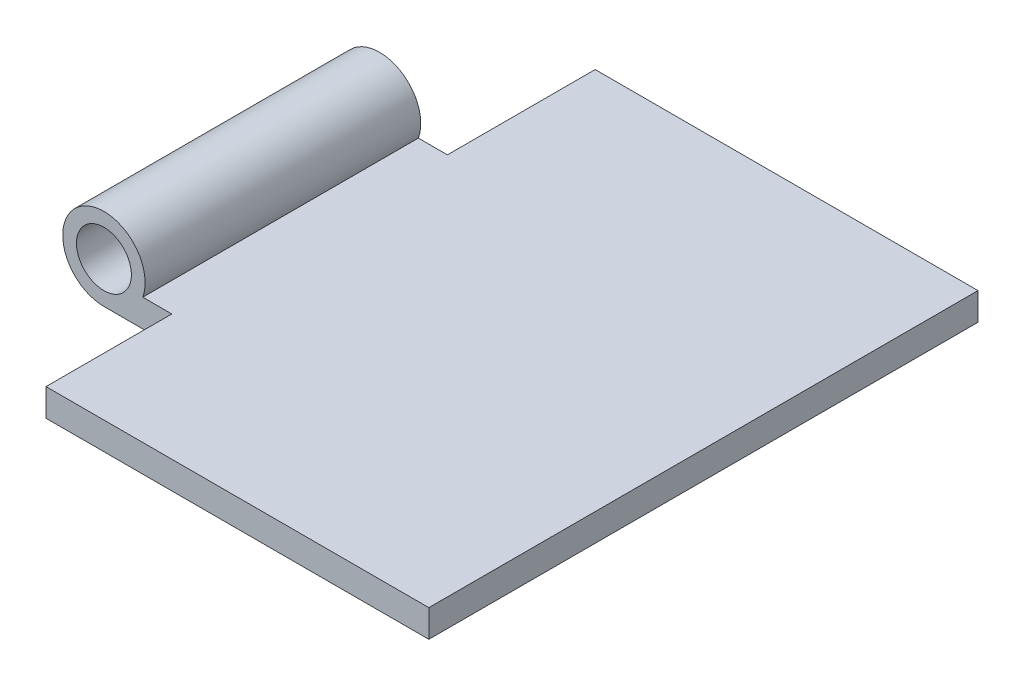
SolidWorks part; units mm, degrees
ref_plane "Спереди" through (0, 0, 0) normal (0, 0, 1) x (1, 0, 0)
ref_plane "Сверху" through (0, 0, 0) normal (0, 1, 0) x (1, 0, 0)
ref_plane "Справа" through (0, 0, 0) normal (1, 0, 0) x (0, 0, -1)
sketch "Эскиз1" plane through (0, 0, 0) normal (0, 0, 1) x (1, 0, 0)
  line L1 (2.8284, -1) -> (32.8284, -1)
  line L3 (0, -3) -> (32.8284, -3)
  line L4 (32.8284, -1) -> (32.8284, -3)
  arc A0 (2.8284, -1) -> (0, -3) centre (0, 0) ccw
  circle A1 centre (0, 0) radius 2
extrude "Вытянуть1" add sketch "Эскиз1" along normal blind 40
sketch "Эскиз2" plane through (0, 0, 0) normal (0, 1, 0) x (1, 0, 0)
  line L5 (4.943, -10.7625) -> (-5.8336, -10.7625)
  line L6 (4.943, -10.7625) -> (4.943, 1.5)
  line L8 (4.943, 1.5) -> (-5.8336, 1.5)
  line L10 (-5.8336, -10.7625) -> (-5.8336, 1.5)
  line L11 (4.943, -30.8379) -> (-5.8336, -30.8379)
  line L12 (4.943, -30.8379) -> (4.943, -42.2757)
  line L13 (4.943, -42.2757) -> (-5.8336, -42.2757)
  line L14 (-5.8336, -30.8379) -> (-5.8336, -42.2757)
extrude "Вытянуть2" cut sketch "Эскиз2" against normal mid plane 40
